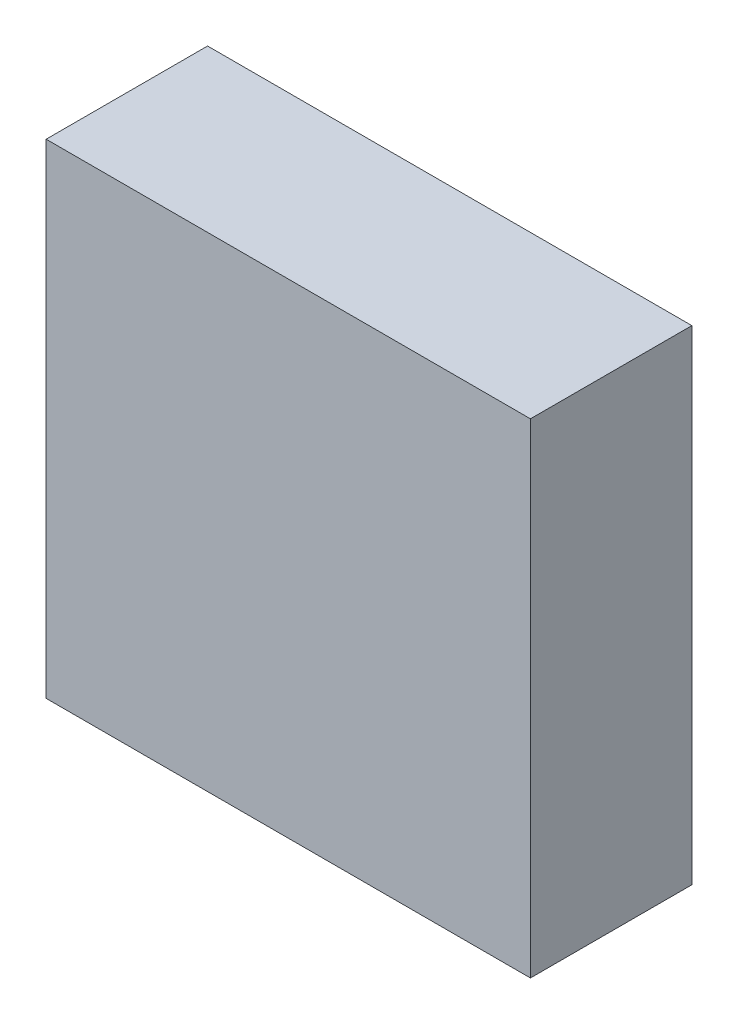
SolidWorks part; units mm, degrees
ref_plane "Front Plane" through (0, 0, 0) normal (0, 0, 1) x (1, 0, 0)
ref_plane "Top Plane" through (0, 0, 0) normal (0, 1, 0) x (1, 0, 0)
ref_plane "Right Plane" through (0, 0, 0) normal (1, 0, 0) x (0, 0, -1)
sketch "Sketch1" plane through (0, 0, 0) normal (0, 0, 1) x (1, 0, 0)
  line L1 (-15, -15) -> (15, -15)
  line L2 (-15, -15) -> (-15, 15)
  line L3 (-15, 15) -> (15, 15)
  line L4 (15, -15) -> (15, 15)
  line L5 (0, 15) -> (0, -15) construction
  line L6 (-15, 0) -> (15, 0) construction
  point P0 (0, 0)
  dimension "D1" = 30
  dimension "D2" = 30
extrude "Boss-Extrude1" add sketch "Sketch1" along normal blind 10
